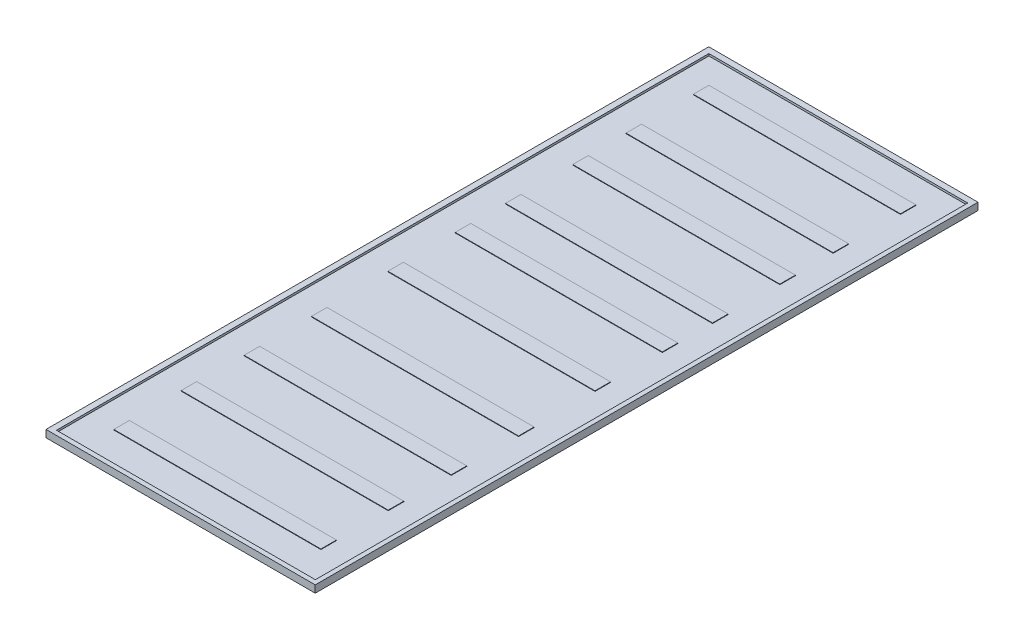
SolidWorks part; units mm, degrees
ref_plane "Front Plane" through (0, 0, 0) normal (0, 0, 1) x (1, 0, 0)
ref_plane "Top Plane" through (0, 0, 0) normal (0, 1, 0) x (1, 0, 0)
ref_plane "Right Plane" through (0, 0, 0) normal (1, 0, 0) x (0, 0, -1)
sketch "Sketch1" plane through (0, 0, 0) normal (0, 1, 0) x (1, 0, 0)
  line L0 (-96.7742, 24.7696) -> (-96.7742, -101.2304)
  line L1 (-96.7742, -101.2304) -> (-46.7742, -101.2304)
  line L2 (-46.7742, -101.2304) -> (-46.7742, 24.7696)
  line L3 (-46.7742, 24.7696) -> (-96.7742, 24.7696)
  dimension "D1" = 126
  dimension "D2" = 50
extrude "Boss-Extrude1" add sketch "Sketch1" along normal blind 0.9974 contours L3 L0 L1 L2
sketch "Sketch2" plane through (0, 0.9974, 0) normal (0, 1, 0) x (1, 0, 0)
  line L0 (-96.7742, -38.2304) -> (-46.7742, -38.2304)
  line L1 (-96.7742, 24.7696) -> (-96.7742, -101.2304) construction
  line L2 (-46.7742, -101.2304) -> (-46.7742, 24.7696) construction
  line L5 (-91.7742, 6.7696) -> (-51.7742, 6.7696)
  line L6 (-51.7742, 6.7696) -> (-51.7742, 3.7696)
  line L7 (-51.7742, 3.7696) -> (-91.7742, 3.7696)
  line L8 (-91.7742, 3.7696) -> (-91.7742, 6.7696)
  line L9 (-91.7742, 16.7696) -> (-51.7742, 16.7696)
  line L10 (-51.7742, 16.7696) -> (-51.7742, 19.7696)
  line L11 (-51.7742, 19.7696) -> (-91.7742, 19.7696)
  line L12 (-91.7742, 19.7696) -> (-91.7742, 16.7696)
  dimension "D2" = 3
  dimension "D3" = 40
  dimension "D4" = 3
extrude "Boss-Extrude2" add sketch "Sketch2" along normal blind 0.1 contours L11 L12 L9 L10 | L8 L7 L6 L5
sketch "Sketch6" plane through (0, 0, 0) normal (0, 1, 0) x (1, 0, 0)
  line L0 (-96.7742, 24.7696) -> (-46.7742, 24.7696)
  line L1 (-46.7742, 24.7696) -> (-46.7742, -101.2304)
  line L2 (-46.7742, -101.2304) -> (-96.7742, -101.2304)
  line L3 (-96.7742, -101.2304) -> (-96.7742, 24.7696)
  line L4 (-97.9212, 25.8941) -> (-45.9212, 25.8941)
  line L5 (-45.9212, 25.8941) -> (-45.9212, -102.1059)
  line L6 (-45.9212, -102.1059) -> (-97.9212, -102.1059)
  line L7 (-97.9212, -102.1059) -> (-97.9212, 25.8941)
  dimension "D1" = 52
  dimension "D2" = 128
extrude "Boss-Extrude8" add sketch "Sketch6" along normal blind 1.4 contours L3 L2 L1 L0 | L7 L4 L5 L6
sketch "Sketch11" plane through (0, 0.9974, 0) normal (0, 1, 0) x (1, 0, 0)
  line L0 (-96.6669, -81.627) -> (-46.6669, -81.627)
  line L5 (-91.6669, -16.627) -> (-51.6669, -16.627)
  line L6 (-51.6669, -16.627) -> (-51.6669, -19.627)
  line L7 (-51.6669, -19.627) -> (-91.6669, -19.627)
  line L8 (-91.6669, -19.627) -> (-91.6669, -16.627)
  line L9 (-91.6669, -6.627) -> (-51.6669, -6.627)
  line L10 (-51.6669, -6.627) -> (-51.6669, -3.627)
  line L11 (-51.6669, -3.627) -> (-91.6669, -3.627)
  line L12 (-91.6669, -3.627) -> (-91.6669, -6.627)
  dimension "D2" = 3
  dimension "D3" = 40
  dimension "D4" = 3
extrude "Boss-Extrude12" add sketch "Sketch11" along normal blind 0.1 contours L11 L12 L9 L10 | L8 L7 L6 L5
sketch "Sketch12" plane through (0, 0.9974, -2.5) normal (0, 1, 0) x (1, 0, 0)
  line L0 (-96.6669, -106.8282) -> (-46.6669, -106.8282)
  line L5 (-91.6669, -41.8282) -> (-51.6669, -41.8282)
  line L6 (-51.6669, -41.8282) -> (-51.6669, -44.8282)
  line L7 (-51.6669, -44.8282) -> (-91.6669, -44.8282)
  line L8 (-91.6669, -44.8282) -> (-91.6669, -41.8282)
  line L9 (-91.6669, -31.8282) -> (-51.6669, -31.8282)
  line L10 (-51.6669, -31.8282) -> (-51.6669, -28.8282)
  line L11 (-51.6669, -28.8282) -> (-91.6669, -28.8282)
  line L12 (-91.6669, -28.8282) -> (-91.6669, -31.8282)
  dimension "D2" = 3
  dimension "D3" = 40
  dimension "D4" = 3
extrude "Boss-Extrude13" add sketch "Sketch12" along normal blind 0.1 contours L11 L12 L9 L10 | L8 L7 L6 L5
sketch "Sketch13" plane through (0, 0.9974, 0) normal (0, 1, 0) x (1, 0, 0)
  line L0 (-96.4989, -132.2665) -> (-46.4989, -132.2665)
  line L5 (-91.4989, -67.2665) -> (-51.4989, -67.2665)
  line L6 (-51.4989, -67.2665) -> (-51.4989, -70.2665)
  line L7 (-51.4989, -70.2665) -> (-91.4989, -70.2665)
  line L8 (-91.4989, -70.2665) -> (-91.4989, -67.2665)
  line L9 (-91.4989, -57.2665) -> (-51.4989, -57.2665)
  line L10 (-51.4989, -57.2665) -> (-51.4989, -54.2665)
  line L11 (-51.4989, -54.2665) -> (-91.4989, -54.2665)
  line L12 (-91.4989, -54.2665) -> (-91.4989, -57.2665)
  dimension "D2" = 3
  dimension "D3" = 40
  dimension "D4" = 3
extrude "Boss-Extrude14" add sketch "Sketch13" along normal blind 0.1 contours L11 L12 L9 L10 | L8 L7 L6 L5
sketch "Sketch14" plane through (0, 0.9974, 0) normal (0, 1, 0) x (1, 0, 0)
  line L0 (-96.6773, -157.2541) -> (-46.6773, -157.2541)
  line L5 (-91.6773, -92.2541) -> (-51.6773, -92.2541)
  line L6 (-51.6773, -92.2541) -> (-51.6773, -95.2541)
  line L7 (-51.6773, -95.2541) -> (-91.6773, -95.2541)
  line L8 (-91.6773, -95.2541) -> (-91.6773, -92.2541)
  line L9 (-91.6773, -82.2541) -> (-51.6773, -82.2541)
  line L10 (-51.6773, -82.2541) -> (-51.6773, -79.2541)
  line L11 (-51.6773, -79.2541) -> (-91.6773, -79.2541)
  line L12 (-91.6773, -79.2541) -> (-91.6773, -82.2541)
  dimension "D2" = 3
  dimension "D3" = 40
  dimension "D4" = 3
extrude "Boss-Extrude15" add sketch "Sketch14" along normal blind 0.1 contours L11 L12 L9 L10 | L8 L7 L6 L5
